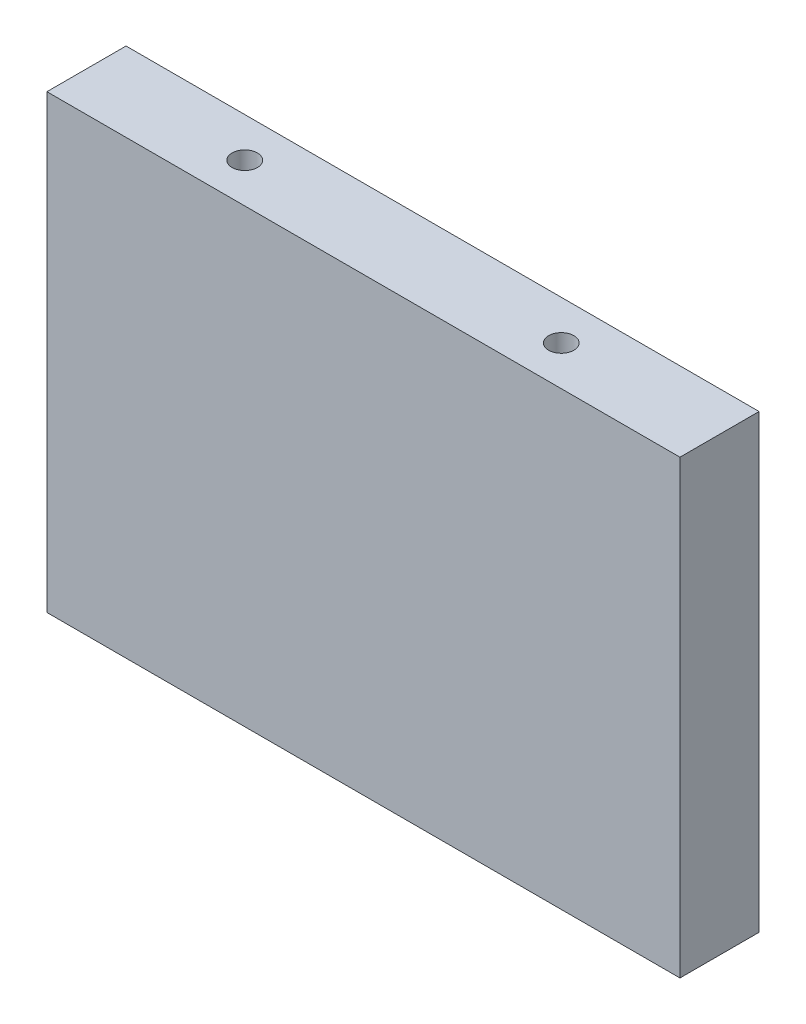
SolidWorks part; units mm, degrees
ref_plane "Front Plane" through (0, 0, 0) normal (0, 0, 1) x (1, 0, 0)
ref_plane "Top Plane" through (0, 0, 0) normal (0, 1, 0) x (1, 0, 0)
ref_plane "Right Plane" through (0, 0, 0) normal (1, 0, 0) x (0, 0, -1)
sketch "Sketch1" plane through (0, 0, 0) normal (0, 0, 1) x (1, 0, 0)
  line L1 (-20, -14.25) -> (20, -14.25)
  line L2 (-20, -14.25) -> (-20, 14.25)
  line L3 (-20, 14.25) -> (20, 14.25)
  line L4 (20, -14.25) -> (20, 14.25)
  line L5 (-20, -14.25) -> (20, 14.25) construction
  line L6 (-20, 14.25) -> (20, -14.25) construction
  point P0 (0, 0)
  dimension "D1" = 40
  dimension "D2" = 28.5
extrude "Boss-Extrude1" add sketch "Sketch1" along normal blind 5
sketch "Sketch2" plane through (0, 14.25, 0) normal (0, 1, 0) x (1, 0, 0)
  line L0 (0, 0) -> (0, -5) construction
  line L1 (20, -5) -> (-20, -5) construction
  line L2 (-20, -2.5) -> (20, -2.5) construction
  line L3 (-20, -5) -> (-20, 0) construction
  line L4 (20, -5) -> (20, 0) construction
  point P11 (-10, -2.5)
  point P12 (10, -2.5)
  dimension "D1" = 10
hole_wizard "M2 Tapped Hole1" positions "Sketch3" profile "Sketch4" tap size "M2" standard "ISO"
sketch "Sketch3" plane through (0, 14.25, 0) normal (0, 1, 0) x (1, 0, 0)
  point P0 (-10, -2.5)
  point P3 (10, -2.5)
sketch "Sketch4" plane through (-10, 14.25, 2.5) normal (1, 0, 0) x (0, 0, 1)
  line L0 (0, 0) -> (0, 5.4807)
  line L1 (0, 5.4807) -> (0.8, 5)
  line L2 (0.8, 5) -> (0.8, 0)
  line L5 (0.8, 0) -> (0, 0)
  line L10 (0, 5.4807) -> (-0.8, 5) construction
  line L11 (0, -6.35) -> (0, 107.95) construction
  dimension "Tap Drill Dia." = 1.6
  dimension "Tap Drill Depth" = 5
  dimension "Drill Angle" = 118
cosmetic thread "Hole Thread1"
cosmetic thread "Hole Thread2"
mirror "Mirror1" about plane through (0, 0, 0) normal (0, 1, 0) of "M2 Tapped Hole1"
cosmetic thread "Hole Thread3"
cosmetic thread "Hole Thread4"
